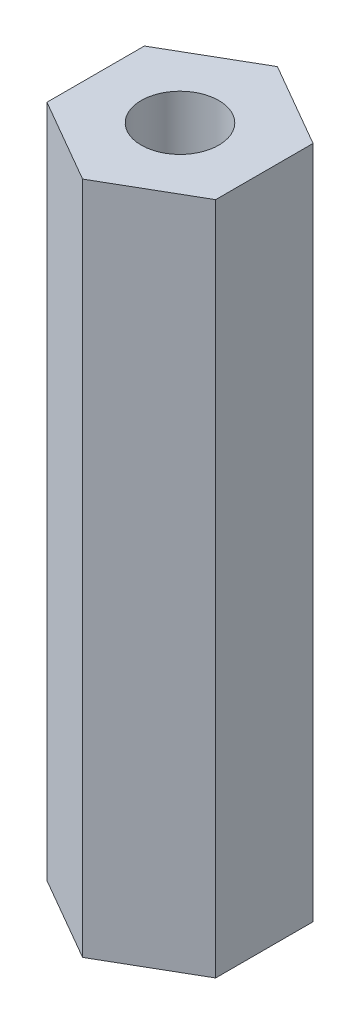
SolidWorks part; units mm, degrees
material "Nylon 6/10"
ref_plane "Front Plane" through (0, 0, 0) normal (0, 0, 1) x (1, 0, 0)
ref_plane "Top Plane" through (0, 0, 0) normal (0, 1, 0) x (1, 0, 0)
ref_plane "Right Plane" through (0, 0, 0) normal (1, 0, 0) x (0, 0, -1)
sketch "Sketch1" plane through (0, 0, 0) normal (0, 1, 0) x (1, 0, 0)
  line L6 (-3.1786, 1.8352) -> (0, 3.6703)
  line L7 (0, 3.6703) -> (3.1786, 1.8351)
  line L8 (3.1786, 1.8351) -> (3.1786, -1.8352)
  line L9 (3.1786, -1.8352) -> (0, -3.6703)
  line L10 (0, -3.6703) -> (-3.1786, -1.8351)
  line L11 (-3.1786, -1.8351) -> (-3.1786, 1.8352)
  circle A0 centre (0, 0) radius 1.4605
  point P12 (0, 0)
extrude "Boss-Extrude1" add sketch "Sketch1" along normal blind 25.4
